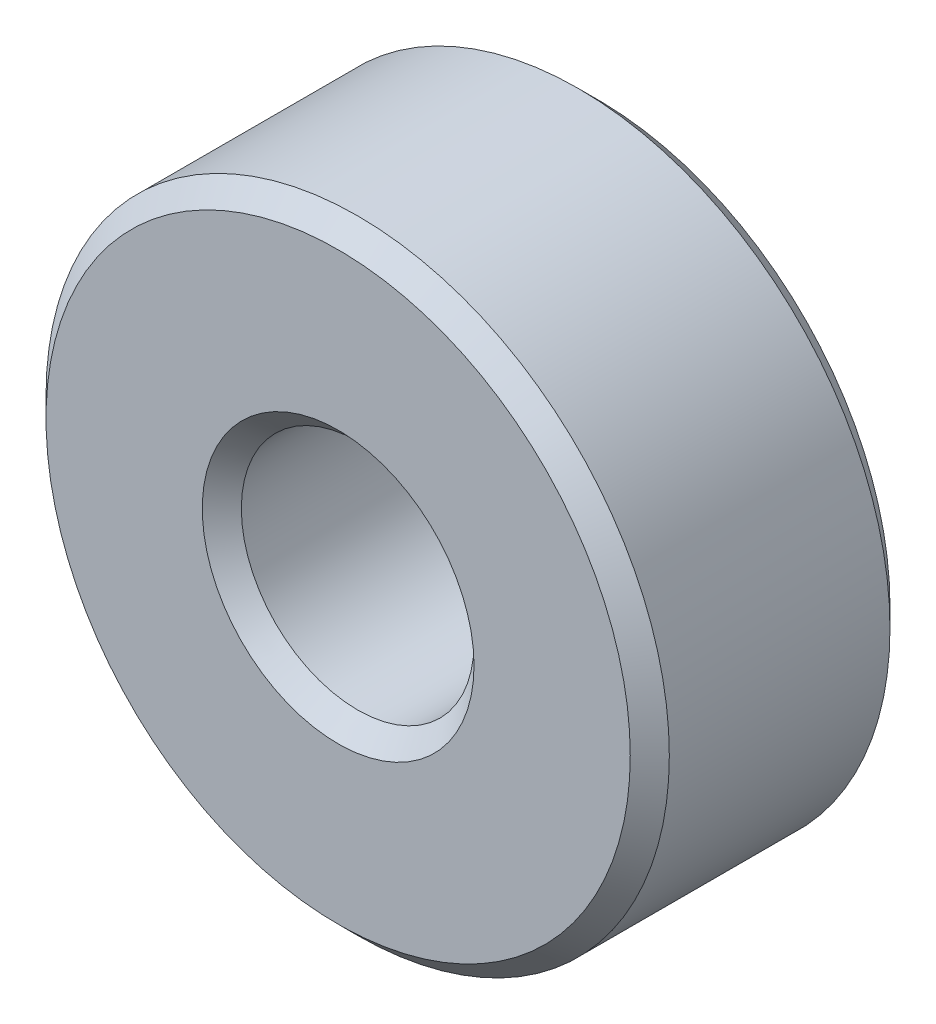
SolidWorks part; units mm, degrees
ref_plane "Front Plane" through (0, 0, 0) normal (0, 0, 1) x (1, 0, 0)
ref_plane "Top Plane" through (0, 0, 0) normal (0, 1, 0) x (1, 0, 0)
ref_plane "Right Plane" through (0, 0, 0) normal (1, 0, 0) x (0, 0, -1)
sketch "Sketch1" plane through (0, 0, 0) normal (0, 0, 1) x (1, 0, 0)
  circle A0 centre (0, 0) radius 4.7625 construction
  circle A1 centre (0, 0) radius 1.778 construction
  point P4 (0, 4.7625)
  dimension "ID" = 3.556
  dimension "OD" = 9.525
sketch "Sketch2" plane through (0, 0, 0) normal (1, 0, 0) x (0, 0, -1)
  line L0 (-1.9844, 4.7625) -> (1.9844, 4.7625) construction
  dimension "Length" = 3.9688
sketch "Sketch3" plane through (0, 0, 0) normal (0, 0, 1) x (1, 0, 0)
  circle A0 centre (0, 0) radius 1.778 construction
  circle A1 centre (0, 0) radius 4.7625 construction
  circle A2 centre (0, 0) radius 1.778
  circle A3 centre (0, 0) radius 4.7625
extrude "Boss-Extrude1" add sketch "Sketch3" against normal up to vertex (1.9844 mm away) and the other way up to vertex (1.9844 mm away) up to point (0, 4.7625, -1.9844) other way up to point (0, 4.7625, 1.9844)
chamfer "Chamfer1" distance 0.2984 angle 45 1 edges at (4.7625, 0, 1.9844)
equation "\"D1@Chamfer1\"=(\"OD@Sketch1\"-\"ID@Sketch1\")*0.05"
